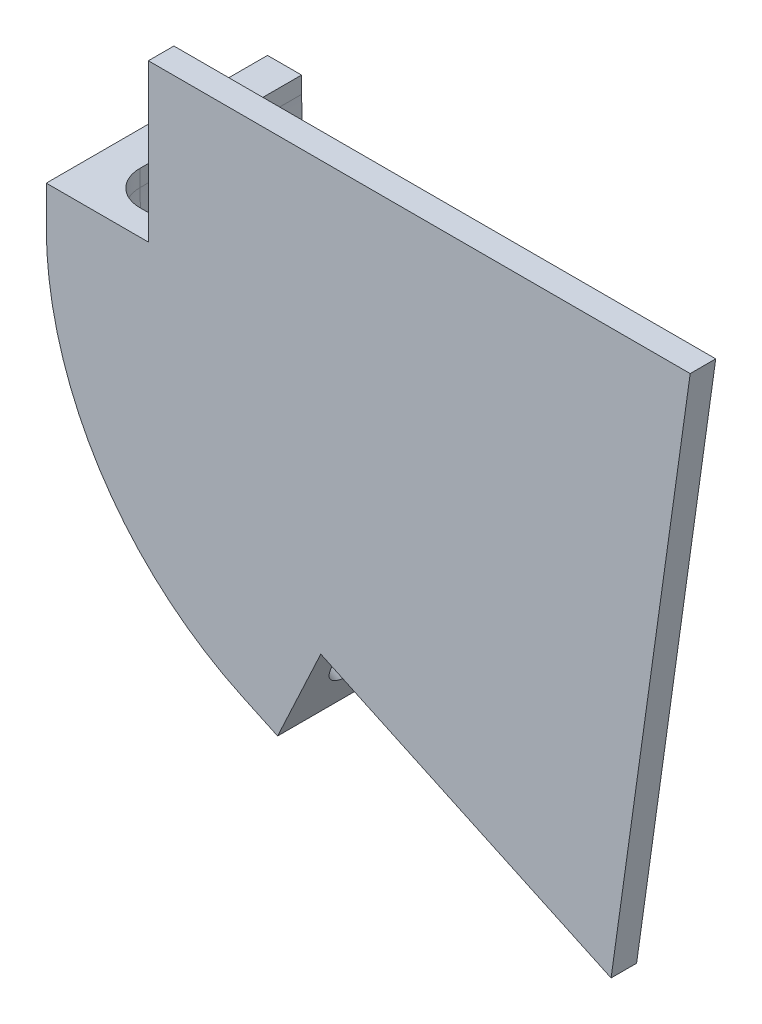
SolidWorks part; units mm, degrees
material "POLYURETHANE (11671)"
ref_plane "Front Plane" through (0, 0, 0) normal (0, 0, 1) x (1, 0, 0)
ref_plane "Top Plane" through (0, 0, 0) normal (0, 1, 0) x (1, 0, 0)
ref_plane "Right Plane" through (0, 0, 0) normal (1, 0, 0) x (0, 0, -1)
sketch "Sketch1" plane through (0, 0, 0) normal (0, 0, 1) x (1, 0, 0)
  line L0 (-4.4818, -31.0063) -> (9.1128, -37.3455)
  line L5 (-18.0764, -4.2621) -> (13.7624, -4.2621)
  line L6 (-18.0764, -4.2621) -> (-18.0764, -9.667)
  line L9 (9.1128, -37.3455) -> (13.7624, -4.2621)
  line L14 (-18.0764, -9.667) -> (-18.0764, -24.667)
  line L15 (-4.4818, -31.0063) -> (-18.0764, -24.667)
  point P12 (0, 0)
  point P13 (0, 0)
  dimension "D4" = 82
  dimension "D3" = 115
extrude "Boss-Extrude1" add sketch "Sketch1" along normal blind 1.5
sketch "Sketch2" plane through (0, 0, 0) normal (0, 0, -1) x (-1, 0, 0)
  line L0 (24.0764, -28.4894) -> (24.0764, -13.4894)
  line L1 (24.0764, -13.4894) -> (17.0764, -13.4894)
  line L2 (17.0764, -13.4894) -> (17.0764, -24.0299)
  line L5 (10.4818, -34.8287) -> (24.0764, -28.4894)
  line L6 (18.0764, -24.667) -> (-9.1128, -37.3455) construction
  line L7 (18.0764, -24.667) -> (-9.1128, -37.3455) construction
  line L8 (7.5235, -28.4845) -> (17.0764, -24.0299)
  line L9 (10.4818, -34.8287) -> (7.5235, -28.4845)
  line L13 (18.0764, -4.2621) -> (18.0764, -24.667) construction
  point P4 (0, 0)
  dimension "D1" = 7
  dimension "D2" = 7
  dimension "D3" = 15
  dimension "D4" = 15
  dimension "D5" = 1
  dimension "D6" = 1
extrude "Boss-Extrude2" add sketch "Sketch2" against normal blind 13
sketch "Sketch4" plane through (0, 0, 13) normal (0, 0, 1) x (1, 0, 0)
  line L0 (-17.0764, -13.4894) -> (-22.0764, -13.4894)
  line L1 (-22.0764, -13.4894) -> (-22.0764, -27.2153)
  line L2 (-22.0764, -27.2153) -> (-9.6365, -33.0161)
  line L3 (-9.6365, -33.0161) -> (-7.5235, -28.4845)
  line L4 (-7.5235, -28.4845) -> (-17.0764, -24.0299)
  line L5 (-17.0764, -24.0299) -> (-17.0764, -13.4894)
  line L6 (-24.0764, -13.4894) -> (-17.0764, -13.4894) construction
  line L7 (-7.5235, -28.4845) -> (-10.4818, -34.8287) construction
  line L8 (-17.0764, -24.0299) -> (-17.0764, -13.4894) construction
  line L9 (-17.0764, -24.0299) -> (-7.5235, -28.4845) construction
  point P8 (0, 0)
  point P12 (0, 0)
  dimension "D1" = 5
  dimension "D2" = 5
extrude "Cut-Extrude3" cut sketch "Sketch4" against normal blind 11.5
fillet "Fillet7" radius 20 2 edges at (-24.0764, -28.4894, 6.5) (-22.0764, -27.2153, 7.25)
fillet "Fillet8" radius 2 3 edges at (-22.0764, -13.9816, 1.5) (-10.0827, -32.808, 1.5) (-18.9442, -25.2199, 1.5)
sketch "Sketch5" plane through (-22.0764, 0, 0) normal (1, 0, 0) x (0, 0, -1)
  line L0 (-13, -13.4894) -> (-13, -14.4739) construction
  line L1 (-3.5, -13.4894) -> (-13, -13.4894) construction
  circle A0 centre (-9, -23.1894) radius 1.6
  dimension "D1" = 3.2
  dimension "D2" = 4
  dimension "D3" = 9.7
extrude "Cut-Extrude4" cut sketch "Sketch5" against normal mid plane 11.5
mirror "Mirror2" about plane through (0, 0, 13) normal (0, 0, 1) of bodies 106
delete or keep bodies "Body-Delete/Keep 1" type keep bodies bodies 108
